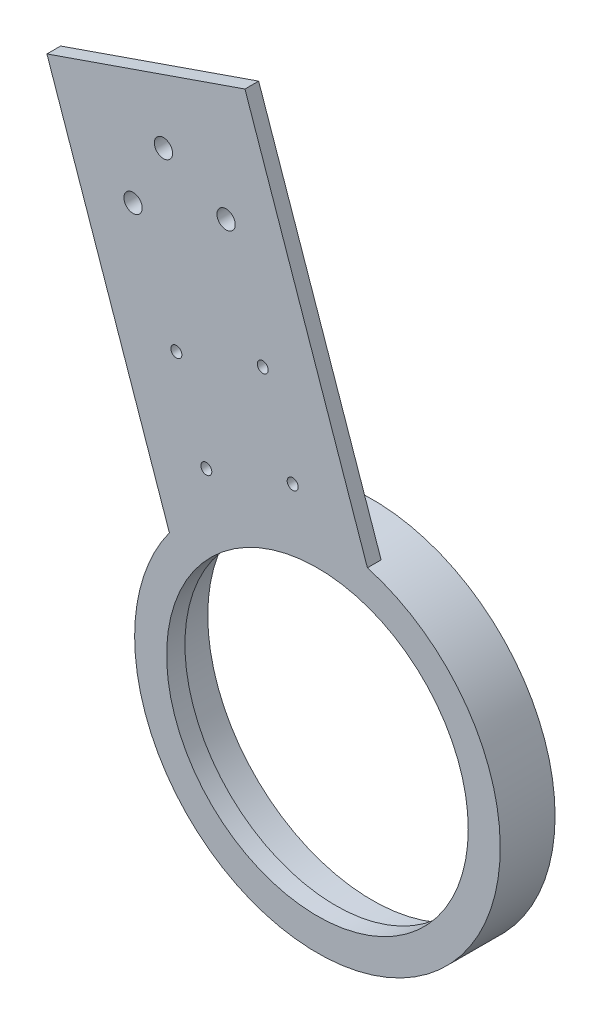
SolidWorks part; units mm, degrees
ref_plane "前视基准面" through (0, 0, 0) normal (0, 0, 1) x (1, 0, 0)
ref_plane "上视基准面" through (0, 0, 0) normal (0, 1, 0) x (1, 0, 0)
ref_plane "右视基准面" through (0, 0, 0) normal (1, 0, 0) x (0, 0, -1)
other "Configuration Table"
sketch "草图1" plane through (0, 0, 0) normal (0, 0, 1) x (1, 0, 0)
  circle A0 centre (-86.6066, -63.7835) radius 33
  circle A1 centre (-86.6066, -63.7835) radius 40
extrude "凸台-拉伸1" add sketch "草图1" along normal blind 4
sketch "草图2" plane through (0, 0, 0) normal (0, 0, -1) x (-1, 0, 0)
  circle A0 centre (86.6066, -63.7835) radius 40
  circle A1 centre (86.6066, -63.7835) radius 36
extrude "凸台-拉伸2" add sketch "草图2" along normal blind 8
sketch "草图4" plane through (0, 0, 4) normal (0, 0, 1) x (1, 0, 0)
  line L0 (-104.6153, -11.8154) -> (-86.6066, -63.7835) construction
  line L2 (-102.4707, 52.0258) -> (-145.8026, 37.0099)
  line L4 (-145.8026, 37.0099) -> (-118.2383, -42.5332)
  line L5 (-102.4707, 52.0258) -> (-74.9064, -27.5173)
  arc A8 (-118.2383, -42.5332) -> (-74.9064, -27.5173) centre (-86.6066, -63.7835) cw
  point P16 (-124.1366, 44.5179)
extrude "凸台-拉伸3" add sketch "草图4" against normal blind 3
sketch "草图6" plane through (0, 0, 1) normal (0, 0, -1) x (-1, 0, 0)
  circle A3 centre (120.3025, 31.9164) radius 2
  circle A4 centre (126.9562, 18.2057) radius 2
  circle A5 centre (106.5917, 25.2627) radius 2
extrude "切除-拉伸1" cut sketch "草图6" against normal blind 3
sketch "草图7" plane through (0, 0, 4) normal (0, 0, 1) x (1, 0, 0)
  circle A0 centre (-117.4745, -5.2482) radius 1.2
  circle A1 centre (-110.9259, -24.1457) radius 1.2
  circle A2 centre (-98.577, 1.3004) radius 1.2
  circle A3 centre (-92.0284, -17.5971) radius 1.2
extrude "切除-拉伸2" cut sketch "草图7" against normal blind 5
